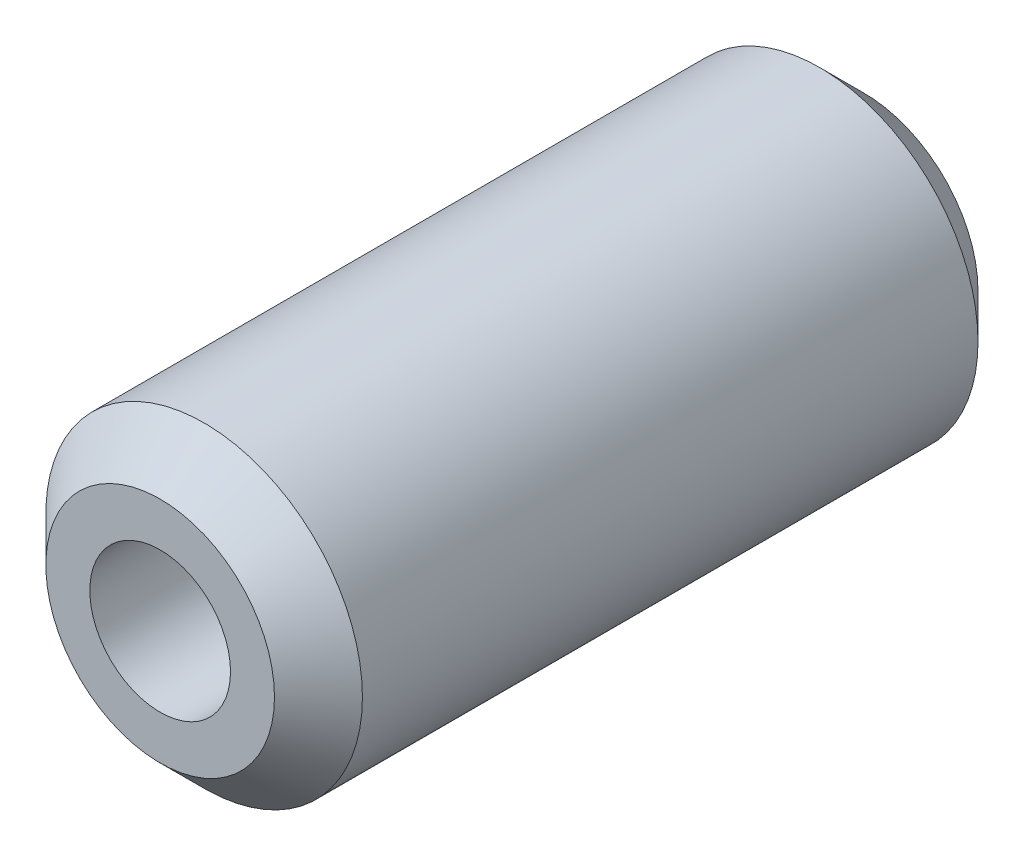
SolidWorks part; units mm, degrees
ref_plane "Front Plane" through (0, 0, 0) normal (0, 0, 1) x (1, 0, 0)
ref_plane "Top Plane" through (0, 0, 0) normal (0, 1, 0) x (1, 0, 0)
ref_plane "Right Plane" through (0, 0, 0) normal (1, 0, 0) x (0, 0, -1)
sketch "Sketch1" plane through (0, 0, 0) normal (0, 0, 1) x (1, 0, 0)
  circle A0 centre (0, 0) radius 9
  circle A1 centre (0, 0) radius 4
  dimension "D1" = 18
  dimension "D2" = 5
extrude "Boss-Extrude1" add sketch "Sketch1" along normal mid plane 40
chamfer "Chamfer1" distance 2.5 angle 45 2 edges at (9, 0, -20) (9, 0, 20)
